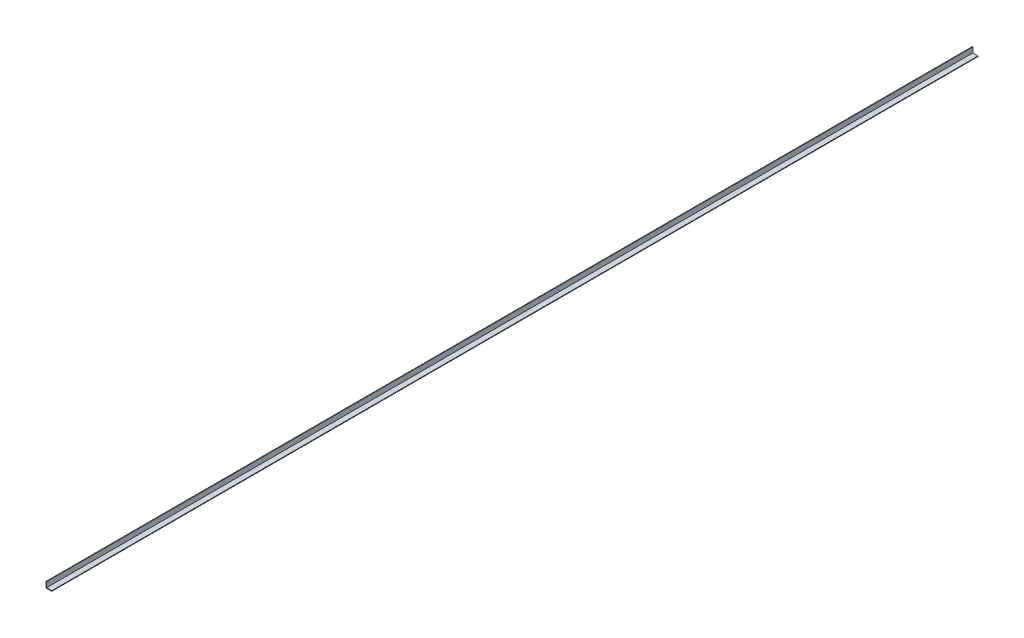
SolidWorks part; units mm, degrees
material "ASTM A36 Acero"
ref_plane "Alzado" through (0, 0, 0) normal (0, 0, 1) x (1, 0, 0)
ref_plane "Planta" through (0, 0, 0) normal (0, 1, 0) x (1, 0, 0)
ref_plane "Vista lateral" through (0, 0, 0) normal (1, 0, 0) x (0, 0, -1)
sketch "Croquis1" plane through (0, 0, 0) normal (0, 0, 1) x (1, 0, 0)
  line L0 (0, 38.1) -> (0, 0)
  line L1 (0, 0) -> (38.1, 0)
  line L2 (38.1, 0) -> (38.1, 3.96)
  line L3 (38.1, 3.96) -> (3.96, 3.96)
  line L4 (3.96, 3.96) -> (3.96, 38.1)
  line L5 (3.96, 38.1) -> (0, 38.1)
  dimension "D1" = 3.96
  dimension "D2" = 38.1
extrude "Saliente-Extruir1" add sketch "Croquis1" against normal blind 6100
